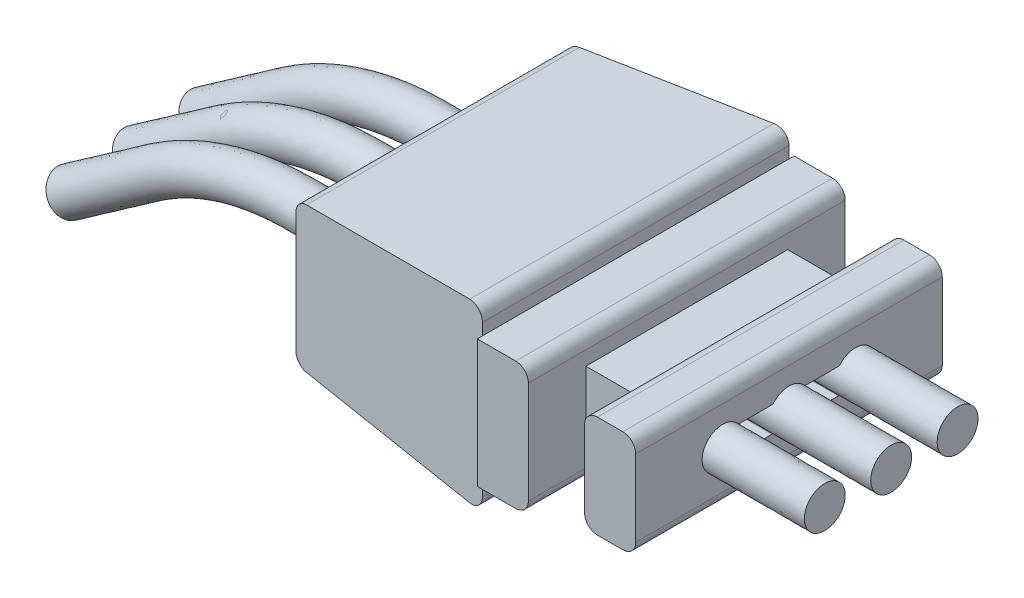
SolidWorks part; units mm, degrees
material "Rubber"
ref_plane "Front Plane" through (0, 0, 0) normal (0, 0, 1) x (1, 0, 0)
ref_plane "Top Plane" through (0, 0, 0) normal (0, 1, 0) x (1, 0, 0)
ref_plane "Right Plane" through (0, 0, 0) normal (1, 0, 0) x (0, 0, -1)
sketch "Sketch1" plane through (0, 0, 0) normal (1, 0, 0) x (0, 0, -1)
  line L1 (-3, 1) -> (3, 1)
  line L2 (-3, 1) -> (-3, -1)
  line L3 (-3, -1) -> (3, -1)
  line L4 (3, 1) -> (3, -1)
  line L5 (-3, 1) -> (3, -1) construction
  line L6 (-3, -1) -> (3, 1) construction
  point P0 (0, 0)
  dimension "D1" = 6
  dimension "D2" = 2
extrude "Boss-Extrude1" add sketch "Sketch1" along normal blind 1
sketch "Sketch2" plane through (0, 0, 0) normal (-1, 0, 0) x (0, 0, 1)
  line L1 (1.975, -0.725) -> (-1.975, -0.725)
  line L2 (1.975, -0.725) -> (1.975, 0.725)
  line L3 (1.975, 0.725) -> (-1.975, 0.725)
  line L4 (-1.975, -0.725) -> (-1.975, 0.725)
  line L5 (1.975, -0.725) -> (-1.975, 0.725) construction
  line L6 (1.975, 0.725) -> (-1.975, -0.725) construction
  point P0 (0, 0)
  dimension "D1" = 3.95
  dimension "D2" = 1.45
extrude "Boss-Extrude2" add sketch "Sketch2" along normal blind 1
sketch "Sketch3" plane through (-1, 0, 0) normal (-1, 0, 0) x (0, 0, 1)
  line L1 (3.1, -1.25) -> (-3.1, -1.25)
  line L2 (3.1, -1.25) -> (3.1, 1.25)
  line L3 (3.1, 1.25) -> (-3.1, 1.25)
  line L4 (-3.1, -1.25) -> (-3.1, 1.25)
  line L5 (3.1, -1.25) -> (-3.1, 1.25) construction
  line L6 (3.1, 1.25) -> (-3.1, -1.25) construction
  point P0 (0, 0)
  dimension "D1" = 6.2
  dimension "D2" = 2.5
extrude "Boss-Extrude3" add sketch "Sketch3" along normal blind 1
sketch "Sketch4" plane through (-2, 0, 0) normal (-1, 0, 0) x (0, 0, 1)
  line L1 (3, -1.75) -> (-3, -1.75)
  line L2 (3, -1.75) -> (3, 1.75)
  line L3 (3, 1.75) -> (-3, 1.75)
  line L4 (-3, -1.75) -> (-3, 1.75)
  line L5 (3, -1.75) -> (-3, 1.75) construction
  line L6 (3, 1.75) -> (-3, -1.75) construction
  point P0 (0, 0)
  dimension "D1" = 6
  dimension "D2" = 3.5
extrude "Boss-Extrude4" add sketch "Sketch4" along normal blind 4 draft 5
fillet "Fillet2" radius 0.25 10 edges at (1, 1, 0) (0, 1, 0) (1, -1, 0) (0, -1, 0) (-6, 1.4, 0) (-1, 1.25, 0) (-6, -1.4, 0) (-1, -1.25, 0) (-2, 1.75, 0) (-2, -1.75, 0)
sketch "Sketch15" plane through (-6, 0, 0) normal (-1, 0, 0) x (0, 0, 1)
  line L0 (0, 0) -> (1.3, 0) construction
  line L1 (0, 0) -> (-1.3, 0) construction
  line L2 (-0.9646, 0.25) -> (-0.3354, 0.25)
  line L3 (-0.9646, -0.25) -> (-0.3354, -0.25)
  line L4 (0.3354, -0.25) -> (0.9646, -0.25)
  line L5 (0.3354, 0.25) -> (0.9646, 0.25)
  arc A0 (0.2981, 0.2667) -> (-0.2981, 0.2667) centre (0, 0) ccw
  arc A1 (1.0019, -0.2667) -> (1.0019, 0.2667) centre (1.3, 0) ccw
  arc A2 (-1.0019, 0.2667) -> (-1.0019, -0.2667) centre (-1.3, 0) ccw
  arc A3 (-0.2981, -0.2667) -> (0.2981, -0.2667) centre (0, 0) ccw
  arc A4 (0.9646, -0.25) -> (1.0019, -0.2667) centre (0.9646, -0.3) cw
  arc A5 (0.2981, -0.2667) -> (0.3354, -0.25) centre (0.3354, -0.3) cw
  arc A6 (0.2981, 0.2667) -> (0.3354, 0.25) centre (0.3354, 0.3) ccw
  arc A7 (0.9646, 0.25) -> (1.0019, 0.2667) centre (0.9646, 0.3) ccw
  arc A8 (-0.3354, -0.25) -> (-0.2981, -0.2667) centre (-0.3354, -0.3) cw
  arc A9 (-0.9646, -0.25) -> (-1.0019, -0.2667) centre (-0.9646, -0.3) ccw
  arc A10 (-0.3354, 0.25) -> (-0.2981, 0.2667) centre (-0.3354, 0.3) ccw
  arc A11 (-0.9646, 0.25) -> (-1.0019, 0.2667) centre (-0.9646, 0.3) cw
  point P20 (0.3122, -0.25)
  point P23 (0.3122, 0.25)
  point P28 (-0.3122, -0.25)
  dimension "D1" = 0.8
  dimension "D7" = 0.05
  dimension "D3" = 1.3
  dimension "D5" = 1.3
  dimension "D6" = 0.5
  dimension "D2" = 2
  dimension "D4" = 2
extrude "Cut-Extrude6" cut sketch "Sketch15" against normal through all
sketch "Sketch10" plane through (0, 0, 0) normal (0, 0, 1) x (1, 0, 0)
  line L0 (1, 0) -> (-7.2735, 0)
  line L2 (1, -0.2667) -> (1, -0.25) construction
  line L3 (-10.1414, -0.9042) -> (-11.7797, -2.0514)
  line L4 (1, 0) -> (3, 0)
  arc A0 (-7.2735, 0) -> (-10.1414, -0.9042) centre (-7.2735, -5) ccw
  dimension "D3" = 5
  dimension "D2" = 145
  dimension "D4" = 2
  dimension "D5" = 2
sweep "Sweep3" add path "Sketch10" circular profile diameter 0.8 parameters "D3"=0.8
pattern_linear "LPattern1" count 2 spacing 1.3 along (0, 0, 1) count 2 spacing 1.3 along (0, 0, -1) of "Sweep3"
